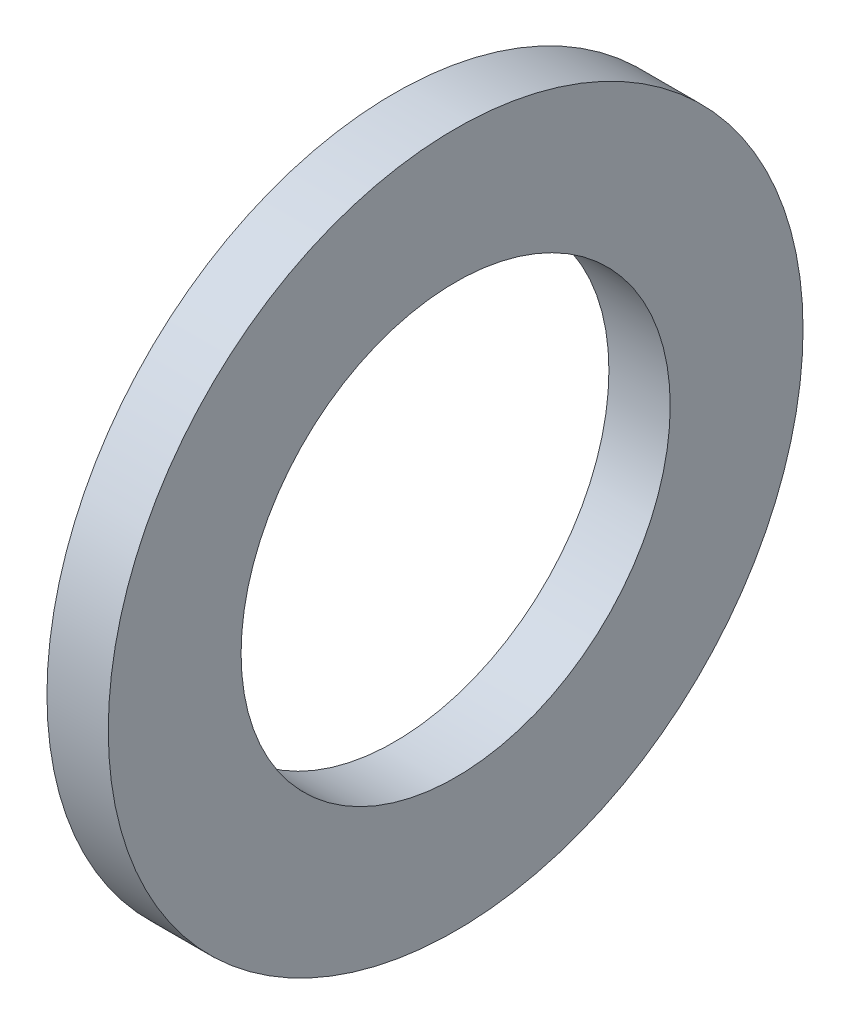
SolidWorks part; units mm, degrees
ref_plane "Plane1" through (0, 0, 0) normal (0, 0, 1) x (1, 0, 0)
ref_plane "Plane2" through (0, 0, 0) normal (0, 1, 0) x (1, 0, 0)
ref_plane "Plane3" through (0, 0, 0) normal (1, 0, 0) x (0, 0, -1)
sketch "Sketch1" plane through (0, 0, 0) normal (0, 0, 1) x (1, 0, 0)
  line L0 (-34.925, 0) -> (9.525, 0) construction
  line L1 (0, 10.5) -> (0, 17)
  line L2 (0, 17) -> (-3, 17)
  line L3 (-3, 17) -> (-3, 10.5)
  line L4 (-3, 10.5) -> (0, 10.5)
  dimension "Thickness" = 3
  dimension "Inside_dia" = 21
  dimension "Outside_dia" = 34
revolve "Base-Revolve" add sketch "Sketch1" angle 360 about L0
